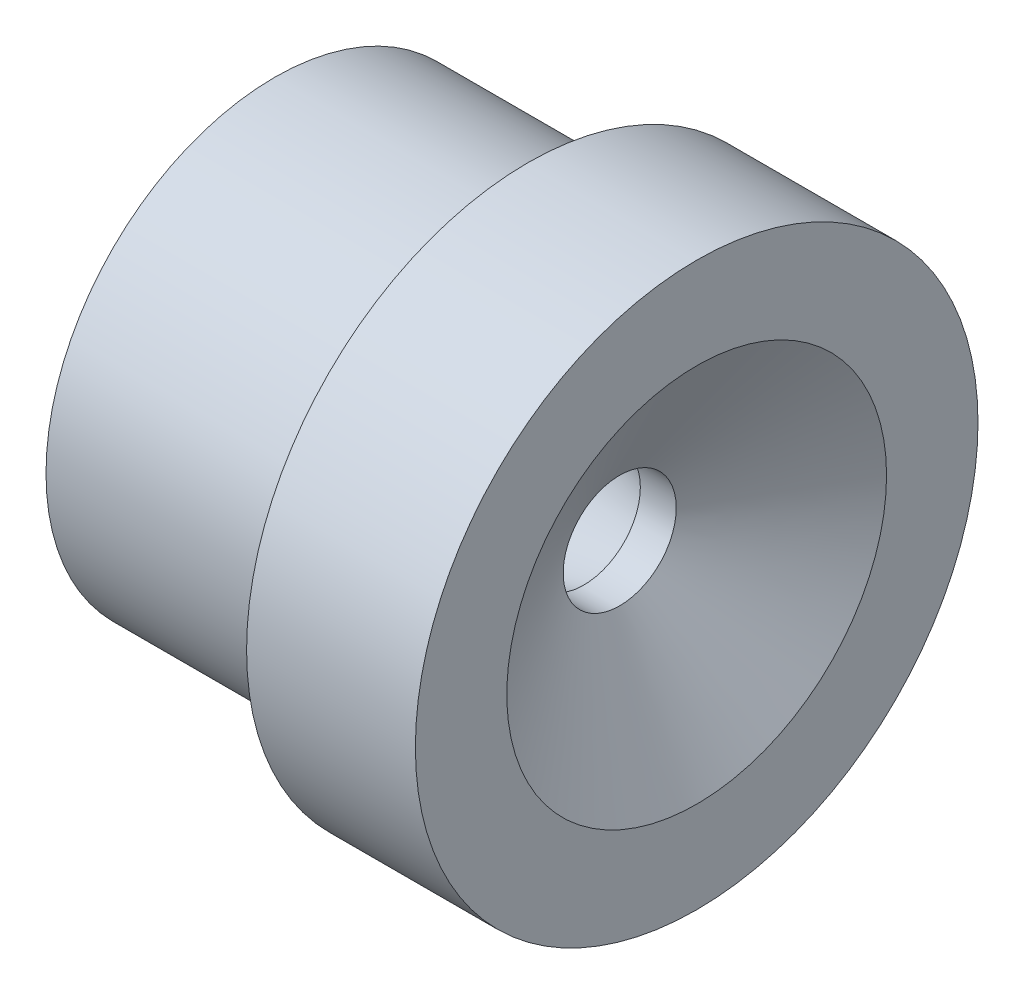
SolidWorks part; units mm, degrees
material "C (Graphite)"
ref_plane "Front Plane" through (0, 0, 0) normal (0, 0, 1) x (1, 0, 0)
ref_plane "Top Plane" through (0, 0, 0) normal (0, 1, 0) x (1, 0, 0)
ref_plane "Right Plane" through (0, 0, 0) normal (1, 0, 0) x (0, 0, -1)
sketch "Sketch1" plane through (0, 0, 0) normal (0, 1, 0) x (1, 0, 0)
  line L0 (0, 0) -> (0, 4.1275)
  line L1 (0, 4.1275) -> (-3.4755, 10.1473)
  line L2 (-3.4755, 10.1473) -> (-5.0961, 10.1473)
  line L3 (-5.0961, 10.1473) -> (-19.05, 6.4084)
  line L4 (-19.05, 6.4084) -> (-19.05, 2.3749)
  line L5 (-19.05, 2.3749) -> (-7.62, 2.3749)
  line L6 (-7.62, 2.3749) -> (-7.62, 0)
  line L9 (-7.62, 0) -> (0, 0)
  line L10 (5.1187, 12.7) -> (-11.0703, 12.7) construction
  dimension "D1" = 25.4
  dimension "D2" = 5.1054
  dimension "D3" = 60
  dimension "D4" = 15
  dimension "D5" = 17.145
  dimension "D6" = 1.6205
  dimension "D7" = 7.62
  dimension "D8" = 19.05
  dimension "D9" = 20.6502
revolve "Revolve1" add sketch "Sketch1" angle 360 about L10
